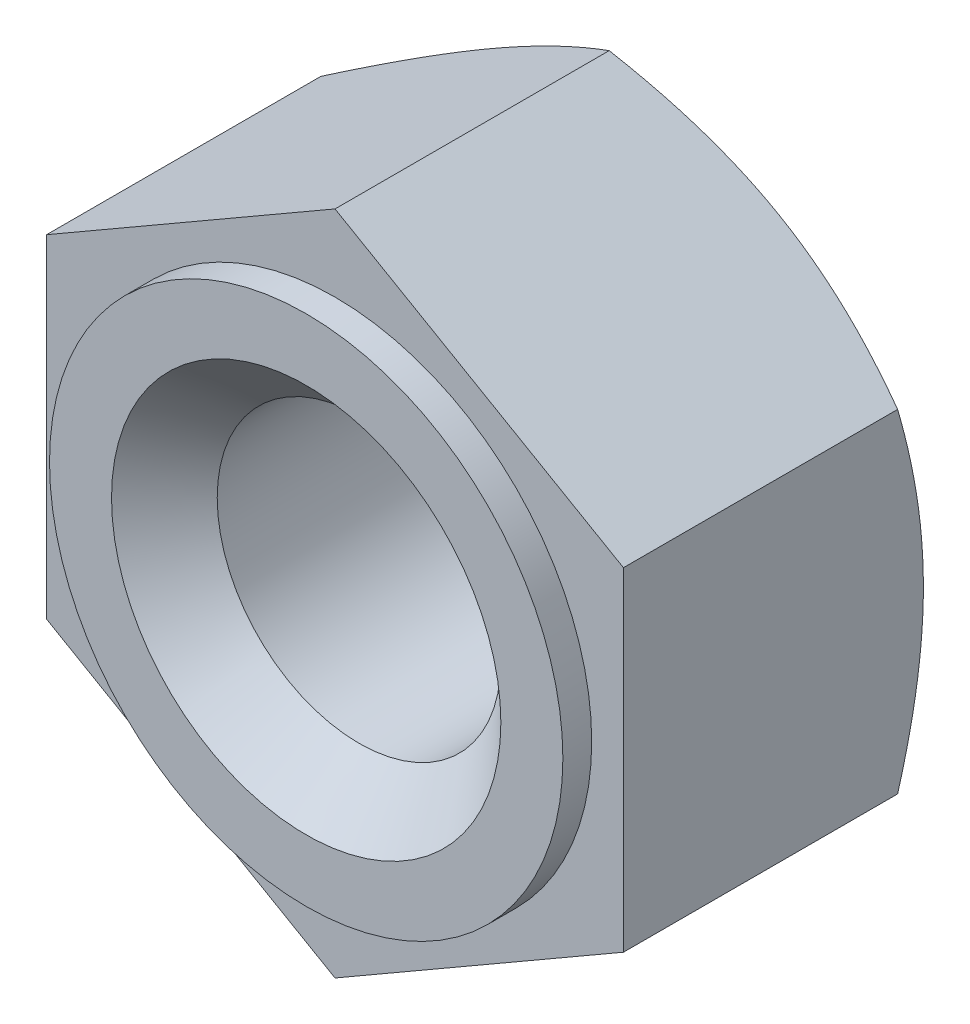
SolidWorks part; units mm, degrees
ref_plane "基准面1" through (0, 0, 0) normal (0, 0, 1) x (1, 0, 0)
ref_plane "基准面2" through (0, 0, 0) normal (0, 1, 0) x (1, 0, 0)
ref_plane "基准面3" through (0, 0, 0) normal (1, 0, 0) x (0, 0, -1)
sketch "尺寸草图" plane through (0, 0, 0) normal (0, 0, 1) x (1, 0, 0)
  line L0 (0, 0) -> (5.7, 0) construction
  line L1 (0, 0) -> (6.75, 0) construction
  line L2 (6.75, 0) -> (15.65, 0) construction
  line L3 (-5.7143, 0) -> (0, 0) construction
  point P0 (-9.23, 0)
  point P3 (6, 0)
  point P4 (0.5, 0)
  point P5 (11.1, 0)
  point P6 (5.7, 0)
  point P8 (10, 0)
  point P15 (2.85, 0)
  point P16 (3.35, 0)
  dimension "D1" = 5.7143
  dimension "D" = 6
  dimension "P" = 0.5
  dimension "e(最小)" = 11.1
  dimension "m(最大)" = 5.7
  dimension "mw" = 3.5157
  dimension "s(最大)" = 10
  dimension "da" = 6.75
  dimension "dw(最小)" = 8.9
  dimension "c" = 0.5
sketch "草图1" plane through (0, 0, 0) normal (0, 0, 1) x (1, 0, 0)
  line L0 (-5, 0) -> (5, 0) construction
  line L1 (0, 5.7735) -> (0, -5.7735) construction
  line L3 (0, 5.7735) -> (-5, 2.8868)
  line L4 (-5, 2.8868) -> (-5, -2.8868)
  line L5 (-5, -2.8868) -> (0, -5.7735)
  line L6 (0, -5.7735) -> (5, -2.8868)
  line L7 (5, -2.8868) -> (5, 2.8868)
  line L8 (5, 2.8868) -> (0, 5.7735)
  circle A0 centre (0, 0) radius 5 construction
  circle A1 centre (0, 0) radius 2.4588
  point P2 (0, 5.3265)
  dimension "D1" = 10
  dimension "D" = 4.9175
  dimension "D2" = 11.1
extrude "基体-拉伸" add sketch "草图1" along normal blind 5.7
cosmetic thread "装饰螺纹线1" parameters "D2"=6
sketch "草图2" plane through (0, 0, 0) normal (0, 0, -1) x (-1, 0, 0)
  circle A0 centre (0, 0) radius 5
  circle A1 centre (0, 0) radius 2.4588 construction
  dimension "s" = 10
extrude "切除-拉伸1" cut sketch "草图2" against normal through all draft 60 flip side to cut
chamfer "倒角1" distance 0.9162 angle 45 2 edges at (2.4588, 0, 0) (2.4588, 0, 5.7)
sketch "草图3" plane through (0, 0, 5.7) normal (0, 0, 1) x (1, 0, 0)
  circle A0 centre (0, 0) radius 5
  dimension "D1" = 10
extrude "切除-拉伸2" cut sketch "草图3" against normal through all draft 60 flip side to cut
sketch "草图4" plane through (0, 0, 5.7) normal (0, 0, 1) x (1, 0, 0)
  circle A0 centre (0, 0) radius 4.45
  circle A1 centre (0, 0) radius 8.9
  dimension "D1" = 8.9
  dimension "D2" = 17.8
extrude "切除-拉伸3" cut sketch "草图4" against normal blind 0.5
